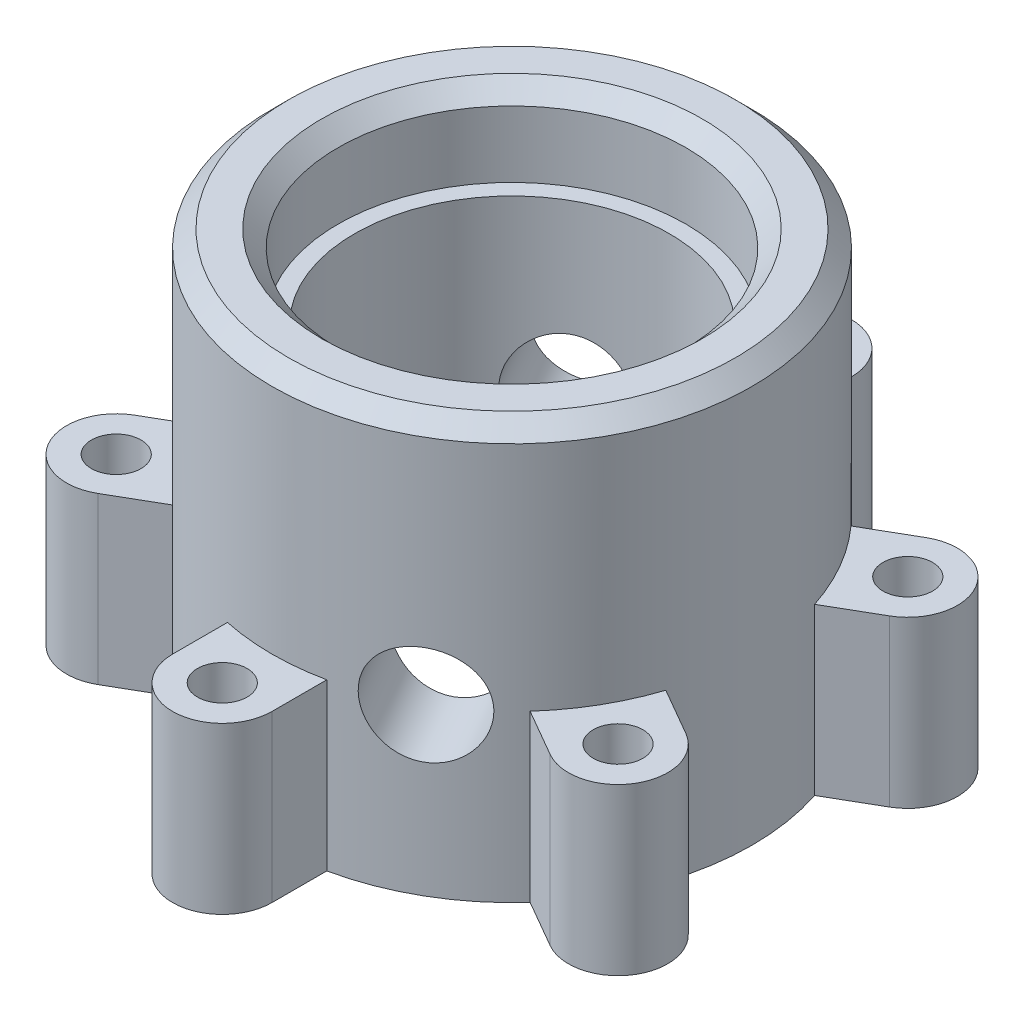
SolidWorks part; units mm, degrees
ref_plane "Front Plane" through (0, 0, 0) normal (0, 0, 1) x (1, 0, 0)
ref_plane "Top Plane" through (0, 0, 0) normal (0, 1, 0) x (1, 0, 0)
ref_plane "Right Plane" through (0, 0, 0) normal (1, 0, 0) x (0, 0, -1)
sketch "Sketch1" plane through (0, 0, 0) normal (0, 1, 0) x (1, 0, 0)
  circle A1 centre (0, 0) radius 14.5
  circle A2 centre (0, 0) radius 9.5
  dimension "D1" = 19
  dimension "D2" = 29
extrude "Boss-Extrude1" add sketch "Sketch1" along normal blind 25
sketch "Sketch2" plane through (0, 0, 0) normal (0, -1, 0) x (1, 0, 0)
  line L0 (0, 0) -> (0, 17.5) construction
  line L1 (0, 0) -> (-17.3205, 10) construction
  line L2 (0, 0) -> (17.3205, 10) construction
  line L3 (0, 0) -> (-17.3205, -10) construction
  line L4 (0, 0) -> (0, -20) construction
  line L5 (0, 0) -> (17.3205, -10) construction
  line L6 (-3, 13.0027) -> (-3, 17.5)
  line L7 (0, 17.5) -> (0, 20.5) construction
  line L10 (-3, 13.0027) -> (3, 13.0027)
  line L11 (3, 13.0027) -> (3, 17.5)
  arc A0 (-17.3205, 10) -> (17.3205, 10) centre (0, 0) ccw construction
  arc A1 (3, 17.5) -> (-3, 17.5) centre (0, 17.5) ccw
  circle A2 centre (0, 17.5) radius 1.5
  circle A3 centre (0, 0) radius 17.5 construction
  point P14 (0, 14.5)
  dimension "D1" = 40
  dimension "D8" = 6
  dimension "D10" = 3
  dimension "D11" = 35
  dimension "D2" = 60
  dimension "D3" = 60
  dimension "D4" = 60
  dimension "D5" = 60
  dimension "D6" = 60
  dimension "D7" = 3
  dimension "D9" = 3
extrude "Boss-Extrude2" add sketch "Sketch2" against normal blind 10
pattern_circular "CirPattern1" count 6 over 360 about axis through (0, 0, 0) along (0, 1, 0) of "Boss-Extrude2"
sketch "Sketch3" plane through (0, 25, 0) normal (0, 1, 0) x (1, 0, 0)
  circle A0 centre (0, 0) radius 10.5
  dimension "D1" = 21
extrude "Cut-Extrude1" cut sketch "Sketch3" against normal blind 5
chamfer "Chamfer1" distance 1 angle 45 1 edges at (0, 25, 10.5)
chamfer "Chamfer2" distance 1 angle 45 1 edges at (0, 25, 14.5)
sketch "Sketch4" plane through (0, 25, 0) normal (0, 1, 0) x (1, 0, 0)
  line L0 (0, 0) -> (7.25, -12.5574) construction
  line L1 (0, 0) -> (0, -14.5) construction
  circle A0 centre (0, 0) radius 14.5 construction
  dimension "D1" = 30
ref_plane "Plane1" through (7.25, 25, 12.5574) normal (0.5, 0, 0.866) x (0.866, 0, -0.5)
sketch "Sketch5" plane through (7.25, 25, 12.5574) normal (0.5, 0, 0.866) x (0.866, 0, -0.5)
  line L0 (0, -1) -> (0, -15) construction
  line L1 (-14.5, -1) -> (14.5, -1) construction
  circle A0 centre (0, -15) radius 3
  dimension "D2" = 6
  dimension "D1" = 14
extrude "Cut-Extrude2" cut sketch "Sketch5" against normal blind 32
